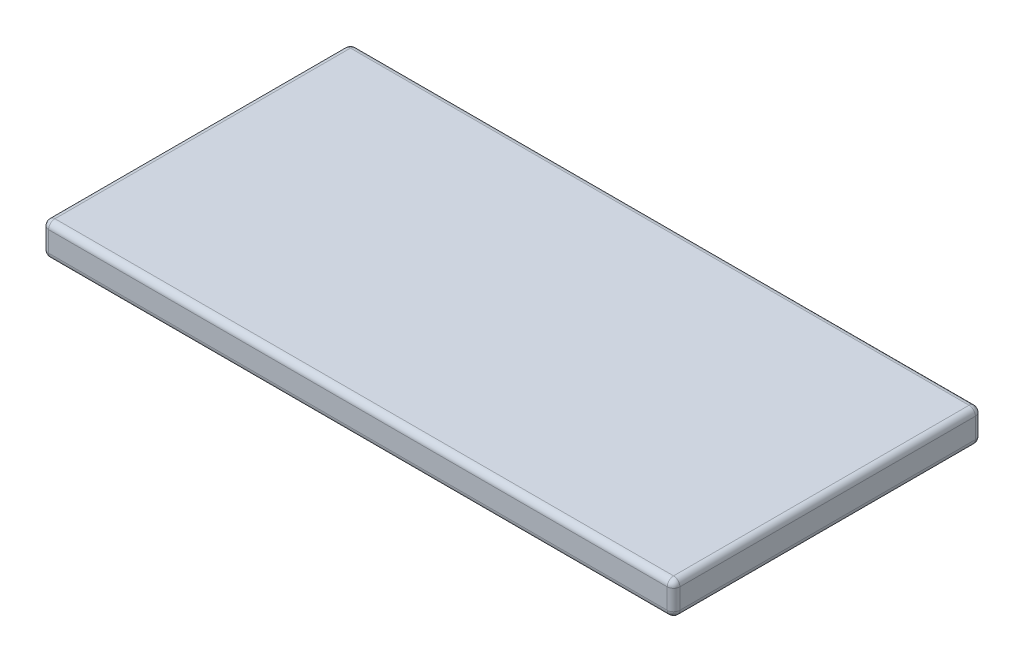
SolidWorks part; units mm, degrees
ref_plane "前视基准面" through (0, 0, 0) normal (0, 0, 1) x (1, 0, 0)
ref_plane "上视基准面" through (0, 0, 0) normal (0, 1, 0) x (1, 0, 0)
ref_plane "右视基准面" through (0, 0, 0) normal (1, 0, 0) x (0, 0, -1)
sketch "草图1" plane through (0, 0, 0) normal (0, 1, 0) x (1, 0, 0)
  line L0 (0, 63.173) -> (0, -47.9571) construction
  line L1 (-49.82, 24.32) -> (49.82, 24.32)
  line L2 (-49.82, 24.32) -> (-49.82, -24.32)
  line L3 (-49.82, -24.32) -> (49.82, -24.32)
  line L4 (49.82, 24.32) -> (49.82, -24.32)
  line L5 (-70.9168, 0) -> (64.3957, 0) construction
  dimension "D1" = 99.64
  dimension "D2" = 48.64
extrude "凸台-拉伸1" add sketch "草图1" along normal blind 5.2
fillet "圆角1" radius 1 12 edges at (-49.82, 2.6, 24.32) (-49.82, 2.6, -24.32) (-49.82, 0, 0) (0, 0, -24.32) (49.82, 2.6, -24.32) (0, 0, 24.32) (49.82, 0, 0) (49.82, 2.6, 24.32) (49.82, 5.2, 0) (0, 5.2, 24.32) (0, 5.2, -24.32) (-49.82, 5.2, 0)
